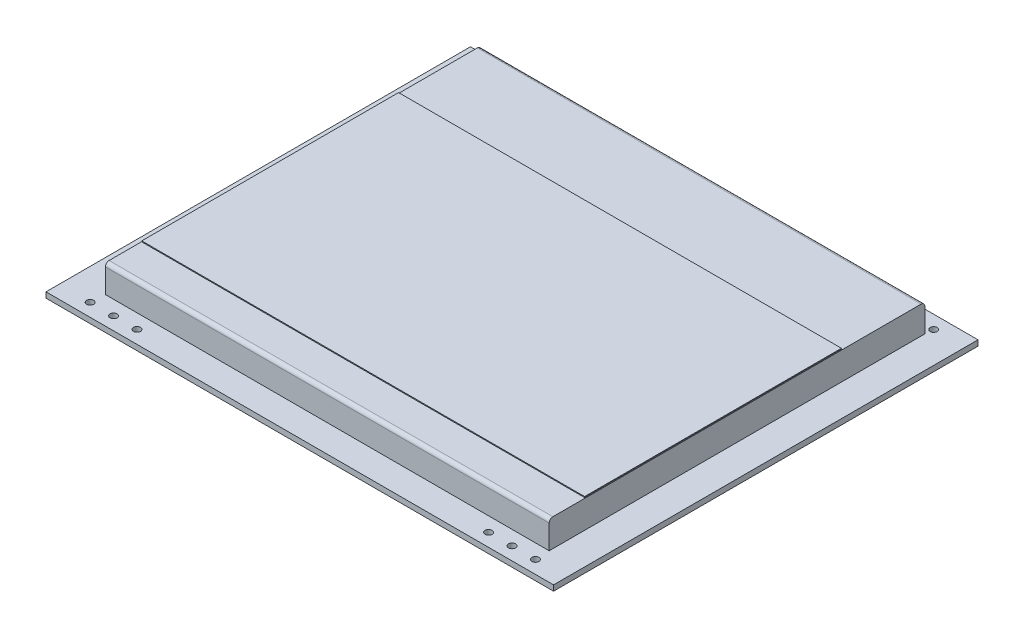
SolidWorks part; units mm, degrees
material "Plastique personnalisé"
ref_plane "Plan de face" through (0, 0, 0) normal (0, 0, 1) x (1, 0, 0)
ref_plane "Plan de dessus" through (0, 0, 0) normal (0, 1, 0) x (1, 0, 0)
ref_plane "Plan de droite" through (0, 0, 0) normal (1, 0, 0) x (0, 0, -1)
sketch "real screen" plane through (0, 0, 0) normal (0, 1, 0) x (1, 0, 0)
  line L1 (-23.995, -13.915) -> (23.995, -13.915)
  line L2 (-23.995, -13.915) -> (-23.995, 13.915)
  line L3 (-23.995, 13.915) -> (23.995, 13.915)
  line L4 (23.995, -13.915) -> (23.995, 13.915)
  line L5 (-23.995, -13.915) -> (23.995, 13.915) construction
  line L6 (-23.995, 13.915) -> (23.995, -13.915) construction
  point P0 (0, 0)
  dimension "D1" = 47.99
  dimension "D2" = 27.83
sketch "cadre ecran" plane through (0, 0, 0) normal (0, 1, 0) x (1, 0, 0)
  line L0 (-23.995, 0) -> (-23.995, 23.8) construction
  line L1 (-23.995, -13.915) -> (-23.995, 13.915) construction
  line L2 (-23.995, 23.8) -> (23.995, 23.8) construction
  line L3 (23.995, 23.8) -> (23.995, -19.38) construction
  line L4 (23.995, -19.38) -> (-23.995, -19.38) construction
  line L5 (-23.995, 23.8) -> (-23.995, 25.21) construction
  line L6 (-23.995, 25.21) -> (23.995, 25.21) construction
  line L7 (-23.995, -19.38) -> (-23.995, -20.7873) construction
  line L8 (-23.995, -20.7873) -> (23.995, -20.7873) construction
  line L9 (0, -20.7873) -> (27.5, -20.7873)
  line L10 (27.5, -20.7873) -> (27.5, 25.21)
  line L11 (27.5, 25.21) -> (-27.5, 25.21)
  line L12 (-27.5, 25.21) -> (-27.5, -20.7873)
  line L13 (-27.5, -20.7873) -> (0, -20.7873)
  dimension "D1" = 23.8
  dimension "D2" = 43.18
  dimension "D3" = 1.41
  dimension "D4" = 55
extrude "Boss.-Extru.1" add sketch "cadre ecran" along normal blind 0.6
sketch "Esquisse3" plane through (0, 0.6, 0) normal (0, 1, 0) x (1, 0, 0)
  line L1 (-24.0204, 22.8745) -> (24.0681, 22.8745)
  line L2 (-24.0204, 22.8745) -> (-24.0204, -17.828)
  line L3 (-24.0204, -17.828) -> (24.0681, -17.828)
  line L4 (24.0681, 22.8745) -> (24.0681, -17.828)
extrude "Boss.-Extru.2" add sketch "Esquisse3" along normal blind 3
fillet "Congé1" radius 0.4 2 edges at (0.0239, 3.6, 17.828) (0.0239, 3.6, -22.8745)
sketch "Esquisse4" plane through (0, 3.6, 0) normal (0, 1, 0) x (1, 0, 0)
  line L1 (-23.995, 13.915) -> (23.995, 13.915)
  line L2 (-23.995, 13.915) -> (-23.995, -13.915)
  line L3 (-23.995, -13.915) -> (23.995, -13.915)
  line L4 (23.995, 13.915) -> (23.995, -13.915)
extrude "Boss.-Extru.3" add sketch "Esquisse4" along normal blind 0.1
sketch "Esquisse5" plane through (-0.1485, 0.6, 0.009) normal (0, 1, 0) x (1, 0, 0)
  line L0 (-23.9763, 23.7832) -> (23.9682, 23.7832) construction
  circle A0 centre (-23.9763, 23.7832) radius 0.381
extrude "Enlèv. mat.-Extru.1" cut sketch "Esquisse5" against normal through all
sketch "Esquisse6" plane through (0, 0.6, 0) normal (0, 1, 0) x (1, 0, 0)
  line L0 (-24.1248, 23.7741) -> (23.8769, 23.7741) construction
pattern_linear "Répétition linéaire1" count 20 spacing 2.54 along (1, 0, 0) of "Enlèv. mat.-Extru.1"
sketch "Esquisse7" plane through (0, 0.6, 0) normal (0, 1, 0) x (1, 0, 0)
  line L0 (-24.1248, 23.7741) -> (-24.1248, -24.5413) construction
  line L1 (-24.1248, -19.3802) -> (27.5, -19.3802) construction
  line L2 (27.5, -20.7873) -> (27.5, 25.21) construction
  circle A0 centre (-24.1248, -19.3802) radius 0.381
  dimension "D1" = 0.762
extrude "Enlèv. mat.-Extru.3" cut sketch "Esquisse7" against normal through all
sketch "Esquisse8" plane through (0, 0.6, 0) normal (0, 1, 0) x (1, 0, 0)
  line L0 (-24.1248, -19.3802) -> (-17.0111, -19.3802)
pattern_linear "Répétition linéaire2" count 3 spacing 2.54 along (1, 0, 0) of "Enlèv. mat.-Extru.3"
sketch "Esquisse9" plane through (0, 0.6, 0) normal (0, 1, 0) x (1, 0, 0)
  line L0 (24.1352, 23.7741) -> (24.1352, -23.7982) construction
  line L1 (-24.1248, -19.3802) -> (24.1352, -19.3802) construction
  circle A0 centre (24.1352, -19.3802) radius 0.381
extrude "Enlèv. mat.-Extru.4" cut sketch "Esquisse9" against normal through all
sketch "Esquisse10" plane through (0, 0.6, 0) normal (0, 1, 0) x (1, 0, 0)
  line L0 (24.1352, -19.3802) -> (21.2754, -19.3802)
pattern_linear "Répétition linéaire3" count 3 spacing 2.54 along (-1, 0, 0) of "Enlèv. mat.-Extru.4"
